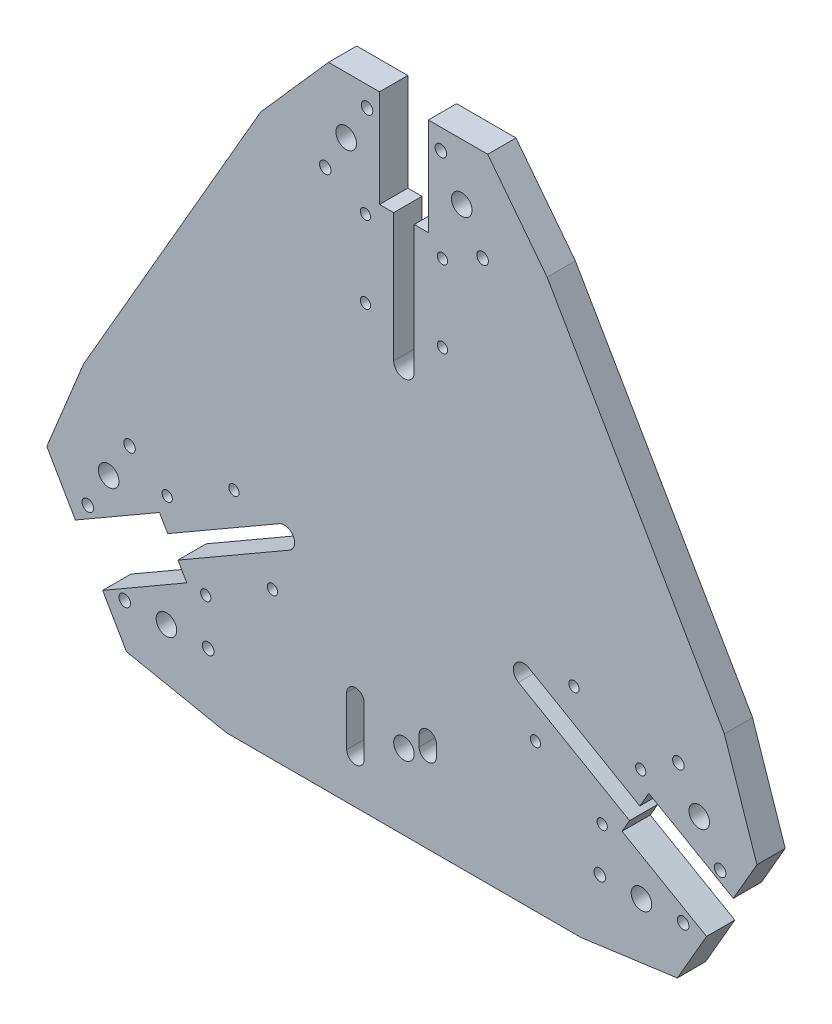
SolidWorks part; units mm, degrees
ref_plane "Plan de face" through (0, 0, 0) normal (0, 0, 1) x (1, 0, 0)
ref_plane "Plan de dessus" through (0, 0, 0) normal (0, 1, 0) x (1, 0, 0)
ref_plane "Plan de droite" through (0, 0, 0) normal (1, 0, 0) x (0, 0, -1)
sketch "Esquisse1" plane through (0, 0, 0) normal (0, 0, 1) x (1, 0, 0)
  line L0 (0, 136.0815) -> (0, 0) construction
  line L1 (0, 0) -> (117.85, -68.0407) construction
  line L2 (0, 0) -> (-117.85, -68.0407) construction
  line L3 (-115, -40.4145) -> (-92.5, -79.3857) construction
  line L4 (-22.5, 119.8002) -> (22.5, 119.8002) construction
  line L5 (92.5, -79.3857) -> (115, -40.4145) construction
  line L6 (55.7583, 111.8894) -> (124.7782, -7.6566)
  line L7 (128.2625, -61.3869) -> (137.4758, -45.429)
  line L8 (9.5, 141.7721) -> (32.6197, 141.7721)
  line L9 (0, 136.0815) -> (0, 159.5946) construction
  line L10 (61, -35.2184) -> (132.0567, -76.243) construction
  line L11 (-117.3404, -80.3045) -> (-108.0806, -96.3431)
  line L12 (-108.0806, -96.3431) -> (-69.0199, -104.2328)
  line L13 (69.0199, -104.2328) -> (-69.0199, -104.2328)
  line L14 (106.4684, -99.1355) -> (69.0199, -104.2328)
  line L15 (117.85, -79.4219) -> (106.4684, -99.1355)
  line L16 (-9.5, 141.7721) -> (-29.3953, 141.7721)
  line L17 (-66.2167, -20.9097) -> (-51.2167, -46.8905) construction
  line L18 (-46.5923, -26.9001) -> (-127.6754, -73.7135) construction
  line L19 (-44.5923, -30.3642) -> (-88.0119, -55.4325)
  line L20 (-92.1974, -35.9097) -> (-77.1974, -61.8905) construction
  line L21 (-48.5923, -23.436) -> (-92.0119, -48.5043)
  line L22 (4, 53.8002) -> (4, 103.7721)
  line L23 (-4, 53.8002) -> (-4, 103.7721)
  line L24 (44.5923, -30.3642) -> (87.8692, -55.3501)
  line L25 (48.5923, -23.436) -> (91.8692, -48.4219)
  line L26 (0, 0) -> (0, -126.5141) construction
  line L27 (-18.9, -67.2857) -> (-18.9, -86.4857) construction
  line L28 (-15.5, -67.2857) -> (-15.5, -86.4857)
  line L29 (-22.3, -67.2857) -> (-22.3, -86.4857)
  line L30 (9.3, -67.2857) -> (9.3, -71.4857) construction
  line L31 (12.7, -67.2857) -> (12.7, -71.4857)
  line L32 (5.9, -67.2857) -> (5.9, -71.4857)
  line L33 (-18.9, -67.2857) -> (9.3, -67.2857) construction
  line L34 (-106.8973, -79.3857) -> (3.3131, -79.3857) construction
  line L35 (137.4758, -45.429) -> (124.7782, -7.6566)
  line L36 (32.6197, 141.7721) -> (55.7583, 111.8894)
  line L37 (-29.3953, 141.7721) -> (-55.7583, 111.8894)
  line L38 (-124.7782, -7.6566) -> (-55.7583, 111.8894)
  line L39 (-139.088, -42.6365) -> (-124.7782, -7.6566)
  line L40 (-127.9718, -61.8905) -> (-139.088, -42.6365)
  line L41 (4, 103.7721) -> (9.5, 103.7721)
  line L42 (-9.5, 103.7721) -> (-4, 103.7721)
  line L43 (-9.5, 103.7721) -> (-9.5, 141.7721)
  line L44 (117.85, -79.4219) -> (84.941, -60.4219)
  line L45 (9.5, 103.7721) -> (9.5, 141.7721)
  line L46 (84.941, -60.4219) -> (87.8692, -55.3501)
  line L47 (95.3536, -42.3869) -> (128.2625, -61.3869)
  line L48 (-127.9718, -61.8905) -> (-95.2055, -42.9728)
  line L49 (91.8692, -48.4219) -> (95.3536, -42.3869)
  line L50 (-95.2055, -42.9728) -> (-92.0119, -48.5043)
  line L51 (-84.5741, -61.3869) -> (-117.3404, -80.3045)
  line L52 (-88.0119, -55.4325) -> (-84.5741, -61.3869)
  circle A0 centre (-92.1974, -35.9097) radius 2
  circle A1 centre (-66.2167, -20.9097) radius 2
  circle A2 centre (-51.2167, -46.8905) radius 2
  circle A3 centre (0, 0) radius 136.0815 construction
  circle A4 centre (-77.1974, -61.8905) radius 2
  arc A5 (-44.5923, -30.3642) -> (-48.5923, -23.436) centre (-46.5923, -26.9001) ccw
  arc A6 (-4, 53.8002) -> (4, 53.8002) centre (0, 53.8002) ccw
  circle A7 centre (-15, 97.8002) radius 2
  circle A8 centre (-15, 67.8002) radius 2
  circle A9 centre (15, 67.8002) radius 2
  circle A10 centre (15, 97.8002) radius 2
  arc A11 (48.5923, -23.436) -> (44.5923, -30.3642) centre (46.5923, -26.9001) ccw
  circle A12 centre (22.5, 119.8002) radius 4
  circle A13 centre (-22.5, 119.8002) radius 4
  circle A14 centre (-115, -40.4145) radius 4
  circle A15 centre (-92.5, -79.3857) radius 4
  circle A16 centre (92.5, -79.3857) radius 4
  circle A17 centre (115, -40.4145) radius 4
  circle A18 centre (92.1974, -35.9097) radius 2
  circle A19 centre (66.2167, -20.9097) radius 2
  circle A20 centre (51.2167, -46.8905) radius 2
  circle A21 centre (77.1974, -61.8905) radius 2
  circle A22 centre (0, -74.8857) radius 4
  arc A23 (-15.5, -67.2857) -> (-22.3, -67.2857) centre (-18.9, -67.2857) ccw
  arc A24 (-22.3, -86.4857) -> (-15.5, -86.4857) centre (-18.9, -86.4857) ccw
  arc A25 (12.7, -67.2857) -> (5.9, -67.2857) centre (9.3, -67.2857) ccw
  arc A26 (5.9, -71.4857) -> (12.7, -71.4857) centre (9.3, -71.4857) ccw
  circle A27 centre (-76.25, -79.3857) radius 2.25
  circle A28 centre (-108.75, -79.3857) radius 2.25
  circle A29 centre (-106.875, -26.3416) radius 2.25
  circle A30 centre (-123.125, -54.4874) radius 2.25
  circle A31 centre (14.375, 133.8731) radius 2.25
  circle A32 centre (30.625, 105.7273) radius 2.25
  circle A33 centre (-14.375, 133.8731) radius 2.25
  circle A34 centre (-30.625, 105.7273) radius 2.25
  circle A35 centre (108.75, -79.3857) radius 2.25
  circle A36 centre (76.25, -79.3857) radius 2.25
  circle A37 centre (123.125, -54.4874) radius 2.25
  circle A38 centre (106.875, -26.3416) radius 2.25
  point P16 (-87.1339, -50.3068)
  point P51 (0, 0)
  point P74 (0, 0)
  point P75 (-18.9, -76.8857)
  point P82 (9.3, -69.3857)
  point P128 (0, 0)
  dimension "D6" = 15
  dimension "D7" = 22
  dimension "D8" = 30
  dimension "D9" = 30
  dimension "D10" = 30
  dimension "D11" = 15
  dimension "D12" = 4
  dimension "D13" = 4
  dimension "D14" = 4
  dimension "D15" = 4
  dimension "D16" = 8
  dimension "D26" = 8
  dimension "D27" = 8
  dimension "D28" = 8
  dimension "D29" = 8
  dimension "D30" = 8
  dimension "D31" = 8
  dimension "D34" = 8
  dimension "D35" = 4.5
  dimension "D43" = 7.6
  dimension "D23" = 4.5
  dimension "D32" = 4.5
  dimension "D4" = 120
  dimension "D5" = 120
  dimension "D17" = 45
  dimension "D18" = 22.5
  dimension "D19" = 45
  dimension "D20" = 22.5
  dimension "D21" = 45
  dimension "D22" = 22.5
  dimension "D24" = 185
  dimension "D25" = 185
  dimension "D33" = 32.5
  dimension "D37" = 66
  dimension "D38" = 4
  dimension "D40" = 6.8
  dimension "D41" = 19.2
  dimension "D42" = 18.9
  dimension "D44" = 6.8
  dimension "D45" = 4.2
  dimension "D46" = 28.2
  dimension "D47" = 16.25
  dimension "D48" = 119.8002
  dimension "D49" = 15
  dimension "D50" = 15
  dimension "D51" = 9.5
  dimension "D52" = 9.5
  dimension "D53" = 38
  dimension "D54" = 38
  dimension "D55" = 9.8564
  dimension "D39" = 3
  dimension "D36" = 3
extrude "Boss.-Extru.1" add sketch "Esquisse1" along normal blind 11
